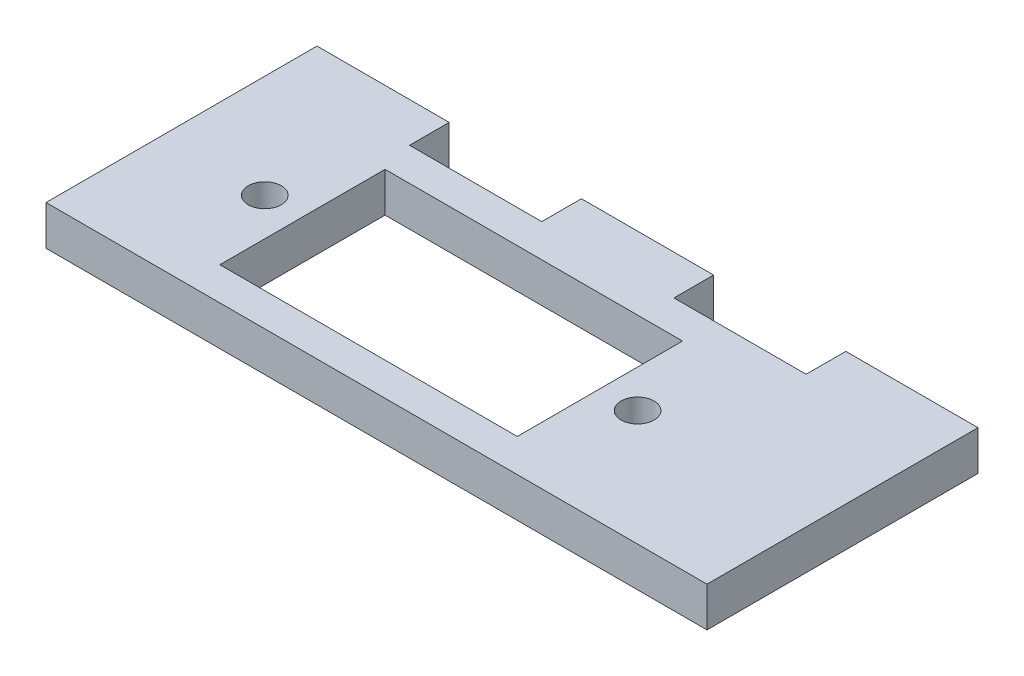
SolidWorks part; units mm, degrees
ref_plane "Alzado" through (0, 0, 0) normal (0, 0, 1) x (1, 0, 0)
ref_plane "Planta" through (0, 0, 0) normal (0, 1, 0) x (1, 0, 0)
ref_plane "Vista lateral" through (0, 0, 0) normal (1, 0, 0) x (0, 0, -1)
sketch "Croquis1" plane through (0, 0, 0) normal (0, 1, 0) x (1, 0, 0)
  line L1 (-25, -8.75) -> (25, -8.75)
  line L2 (-25, -8.75) -> (-25, 8.75)
  line L3 (-25, 8.75) -> (25, 8.75)
  line L4 (25, -8.75) -> (25, 8.75)
  line L5 (-25, -8.75) -> (25, 8.75) construction
  line L6 (-25, 8.75) -> (25, -8.75) construction
  line L16 (-14.35, 6.25) -> (8.15, 6.25)
  line L17 (-14.35, 6.25) -> (-14.35, -6.25)
  line L18 (-14.35, -6.25) -> (8.15, -6.25)
  line L19 (8.15, 6.25) -> (8.15, -6.25)
  line L20 (-14.35, 6.25) -> (8.15, -6.25) construction
  line L21 (-14.35, -6.25) -> (8.15, 6.25) construction
  line L48 (0, 0) -> (9.9901, 0) construction
  line L50 (-25, 8.75) -> (-15, 8.75)
  line L51 (-25, 8.75) -> (-25, 11.75)
  line L52 (-25, 11.75) -> (-15, 11.75)
  line L53 (-15, 8.75) -> (-15, 11.75)
  line L54 (-5, 8.75) -> (-5, 11.75)
  line L55 (-5, 8.75) -> (5, 8.75)
  line L56 (5, 8.75) -> (5, 11.75)
  line L57 (-5, 11.75) -> (5, 11.75)
  line L58 (15, 8.75) -> (15, 11.75)
  line L59 (15, 8.75) -> (25, 8.75)
  line L60 (25, 8.75) -> (25, 11.75)
  line L61 (15, 11.75) -> (25, 11.75)
  circle A1 centre (11, 0) radius 1.25
  circle A2 centre (-17.2, 0) radius 1.25
  point P0 (0, 0)
  point P16 (-3.1, 0)
  dimension "D3" = 7.8
  dimension "D5" = 2.5
  dimension "D11" = 3
  dimension "D1" = 50
  dimension "D2" = 17.5
  dimension "D4" = 3
  dimension "D7" = 28.2
  dimension "D8" = 22.5
  dimension "D9" = 12.5
  dimension "D10" = 10
  dimension "D6" = 14.1
extrude "Saliente-Extruir1" add sketch "Croquis1" along normal blind 3
